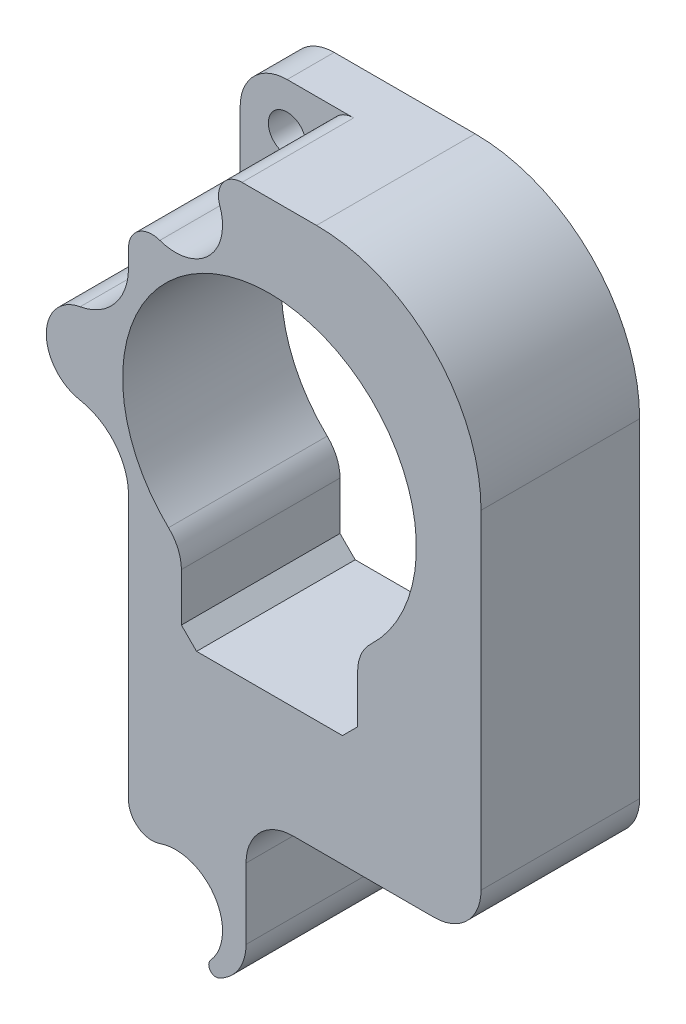
SolidWorks part; units mm, degrees
ref_plane "前视基准面" through (0, 0, 0) normal (0, 0, 1) x (1, 0, 0)
ref_plane "上视基准面" through (0, 0, 0) normal (0, 1, 0) x (1, 0, 0)
ref_plane "右视基准面" through (0, 0, 0) normal (1, 0, 0) x (0, 0, -1)
ref_plane "基准面1" through (0, 0, 17) normal (0, 0, 1) x (1, 0, 0)
sketch "草图1" plane through (0, 0, 17) normal (0, 0, 1) x (1, 0, 0)
  line L0 (13.5, -30) -> (19.5, -30)
  line L1 (23.5, -26) -> (23.5, 18.8666)
  line L2 (23.5, 18.8666) -> (13.5, 18.8666)
  line L3 (13.5, 2.1334) -> (13.5, -30)
  arc A0 (19.5, -30) -> (23.5, -26) centre (19.5, -26) ccw
  arc A1 (13.5, 18.8666) -> (9.3824, 13.9451) centre (8.5, 18.8666) cw
  arc A2 (9.3824, 13.9451) -> (9.3824, 7.0549) centre (10, 10.5) ccw
  arc A3 (9.3824, 7.0549) -> (13.5, 2.1334) centre (8.5, 2.1334) cw
  dimension "D1" = 4
  dimension "D2" = 5
  dimension "D3" = 3.5
  dimension "D4" = 10
  dimension "D5" = 13.5
  dimension "D6" = 32.1334
extrude "凸台-拉伸1" add sketch "草图1" against normal blind 13.5
sketch "草图2" plane through (0, 0, 17) normal (0, 0, 1) x (1, 0, 0)
  line L0 (13.5, -20.3431) -> (13.5, -30)
  line L1 (13.5, -30) -> (19.5, -30)
  line L2 (13.5, 2.1334) -> (13.5, -30) construction
  line L3 (13.5, -30) -> (19.5, -30) construction
  arc A0 (21.1928, -29.6242) -> (20.4814, -28.6667) centre (20.9351, -29.0726) cw
  arc A1 (20.4814, -28.6667) -> (16.1667, -22.2288) centre (17.5, -26) ccw
  arc A2 (16.1667, -22.2288) -> (13.5, -20.3431) centre (15.5, -20.3431) cw
  arc A3 (19.5, -30) -> (21.1928, -29.6242) centre (19.5, -26) ccw
  dimension "D1" = 0.6088
  dimension "D2" = 4
  dimension "D3" = 2
  dimension "D4" = 4
  dimension "D5" = 2
  dimension "D6" = 2.6667
  dimension "D7" = 6
  dimension "D8" = 0.3758
extrude "切除-拉伸1" cut sketch "草图2" against normal blind 9.5
sketch "草图3" plane through (0, 18.8666, 0) normal (0, 1, 0) x (-1, 0, 0)
  line L0 (-23.5, 17) -> (-13.5, 17)
  line L1 (-13.5, 17) -> (-13.5, 3.5)
  line L2 (-13.5, 3.5) -> (-23.5, 3.5)
  line L3 (-23.5, 3.5) -> (-23.5, 17)
  line L4 (-23.5, 3.5) -> (-23.5, 17) construction
  line L5 (-23.5, 17) -> (-13.5, 17) construction
  dimension "D1" = 10
  dimension "D2" = 13.5
extrude "凸台-拉伸2" add sketch "草图3" along normal blind 11.1334
sketch "草图4" plane through (23.5, 0, 0) normal (1, 0, 0) x (0, 0, -1)
  line L0 (-3.5, 30) -> (-3.5, -16)
  line L1 (-3.5, -16) -> (-17, -16)
  line L2 (-17, -16) -> (-17, 30)
  line L3 (-17, 30) -> (-3.5, 30)
  line L4 (-17, -26) -> (-17, 30) construction
  line L5 (-3.5, -26) -> (-17, -26) construction
  dimension "D1" = 13.5
  dimension "D2" = 10
  dimension "D3" = 56
extrude "凸台-拉伸3" add sketch "草图4" along normal blind 20
sketch "草图5" plane through (0, 0, 17) normal (0, 0, 1) x (1, 0, 0)
  line L0 (23.1569, 30) -> (13.5, 30)
  line L1 (13.5, 30) -> (13.5, 20.3431)
  line L2 (43.5, 30) -> (43.5, -16) construction
  line L3 (43.5, -16) -> (23.5, -16) construction
  arc A0 (13.5, 20.3431) -> (16.1667, 22.2288) centre (15.5, 20.3431) cw
  arc A1 (16.1667, 22.2288) -> (21.2712, 27.3333) centre (17.5, 26) ccw
  arc A2 (21.2712, 27.3333) -> (23.1569, 30) centre (23.1569, 28) cw
  dimension "D1" = 2
  dimension "D2" = 4
  dimension "D3" = 2
  dimension "D4" = 20.3431
  dimension "D5" = 22.2288
  dimension "D6" = 27.3333
  dimension "D7" = 36.3431
extrude "切除-拉伸2" cut sketch "草图5" against normal blind 9.5
sketch "草图6" plane through (0, 0, 3.5) normal (0, 0, -1) x (-1, 0, 0)
  line L0 (-33, -6.5) -> (-18, -6.5)
  line L1 (-18, -6.5) -> (-18, 0.5)
  line L2 (-33, 0.5) -> (-33, -6.5)
  line L3 (-13.5, 2.1334) -> (-13.5, -30) construction
  line L4 (-43.5, 30) -> (-13.5, 30) construction
  arc A0 (-18, 0.5) -> (-33, 0.5) centre (-25.5, 10.5) cw
  dimension "D1" = 12.5
  dimension "D2" = 4.5
  dimension "D3" = 12
  dimension "D4" = 19.5
  dimension "D6" = 36.5
extrude "切除-拉伸3" cut sketch "草图6" against normal through all
ref_plane "基准面2" through (0, 10.5, 0) normal (0, 1, 0) x (1, 0, 0)
sketch "草图7" plane through (0, 10.5, 0) normal (0, 1, 0) x (1, 0, 0)
  line L0 (38, -3.5) -> (25.5, -3.5)
  line L1 (25.5, -3.5) -> (25.5, -17)
  line L2 (25.5, -17) -> (38, -17)
  line L3 (38, -17) -> (38, -3.5)
  line L4 (25.5, -3.5) -> (25.5, -17) construction
  dimension "D1" = 12.5
  dimension "D2" = 13.5
revolve "切除-旋转1" cut sketch "草图7" angle 360 about L4
hole_wizard "Ø3.2 (3.2) 直径孔1" positions "草图9" profile "草图8" hole size "Ø3.2" standard "ANSI Metric"
sketch "草图9" plane through (0, 0, 3.5) normal (0, 0, -1) x (-1, 0, 0)
  point P0 (-17.5, 26)
  point P1 (-17.5, -26)
sketch "草图8" plane through (17.5, 26, 3.5) normal (1, 0, 0) x (0, 1, 0)
  line L0 (0, 0) -> (0, 13.5)
  line L1 (0, 13.5) -> (1.6, 13.5)
  line L2 (1.6, 13.5) -> (1.6, 0)
  line L5 (1.6, 0) -> (0, 0)
  line L11 (0, -6.35) -> (0, 107.95) construction
  dimension "通孔孔直径" = 3.2
  dimension "通孔孔深度" = 13.5
chamfer "倒角1" distance 1.2929 angle 45 2 edges at (33, -6.5, 10.25) (18, -6.5, 10.25)
fillet "圆角1" radius 3.5 2 edges at (33, 0.5, 10.25) (18, 0.5, 10.25)
fillet "圆角2" radius 4 4 edges at (43.5, -16, 10.25) (13.5, 30, 5.5) (23.5, -16, 10.25) (13.5, -30, 5.5)
fillet "圆角3" radius 14 1 edges at (43.5, 30, 10.25)
